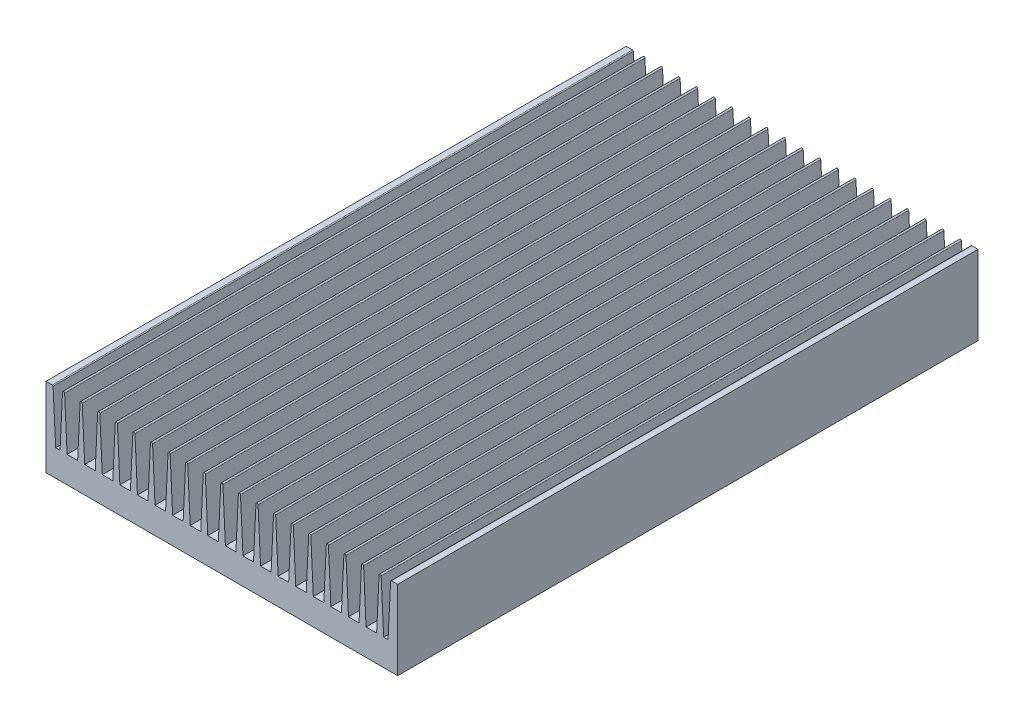
SolidWorks part; units mm, degrees
ref_plane "Спереди" through (0, 0, 0) normal (0, 0, 1) x (1, 0, 0)
ref_plane "Сверху" through (0, 0, 0) normal (0, 1, 0) x (1, 0, 0)
ref_plane "Справа" through (0, 0, 0) normal (1, 0, 0) x (0, 0, -1)
sketch "Эскиз1" plane through (0, 0, 0) normal (0, 0, 1) x (1, 0, 0)
  line L0 (0, 45) -> (3.5244, 45)
  line L1 (0, 0) -> (200, 0)
  line L2 (4.0238, 44.525) -> (5.5, 15)
  line L3 (0, 45) -> (0, 0)
  line L4 (200, 45) -> (200, 0)
  line L5 (100, 63.7127) -> (100, -22.2582) construction
  line L8 (200, 45) -> (196.4756, 45)
  line L9 (195.9762, 44.525) -> (194.5, 15)
  line L10 (5.5, 15) -> (194.5, 15)
  arc A0 (3.5244, 45) -> (4.0238, 44.525) centre (3.5244, 44.5) cw
  arc A2 (196.4756, 45) -> (195.9762, 44.525) centre (196.4756, 44.5) ccw
  point P18 (196, 45)
  dimension "D9" = 0.5
  dimension "D1" = 200
  dimension "D2" = 15
  dimension "D3" = 5.5
  dimension "D4" = 45
  dimension "D7" = 4
extrude "Вытянуть1" add sketch "Эскиз1" along normal blind 330
sketch "Эскиз2" plane through (0, 0, 330) normal (0, 0, 1) x (1, 0, 0)
  line L0 (194.5, 15) -> (5.5, 15) construction
  line L1 (9.4007, 44.4285) -> (8, 15)
  line L2 (10, 45) -> (10, 22.5548) construction
  line L3 (10.5993, 44.4285) -> (12, 15)
  line L4 (8, 15) -> (12, 15)
  line L6 (0, 45) -> (0, 0) construction
  arc A0 (9.4007, 44.4285) -> (10.5993, 44.4285) centre (10, 44.4) cw
  dimension "D1" = 30
  dimension "D3" = 0.6
  dimension "D2" = 4
  dimension "D4" = 10
extrude "Вытянуть3" add sketch "Эскиз2" against normal blind 330
pattern_curve "Кривая1" of "Вытянуть3" along edge at (100, 0, 0) parameters "D1"=19, "D3"=10, "D2"=1, "D4"=50
sketch "Эскиз3" plane through (0, 0, 0) normal (0, -1, 0) x (1, 0, 0)
  line L2 (0, 0) -> (200, 0) construction
  line L3 (0, 330) -> (0, 0) construction
  line L4 (200, 330) -> (200, 0) construction
  circle A0 centre (9.5, 19.5) radius 2.1
  circle A1 centre (11.5, 151) radius 2.1
  circle A2 centre (16.5, 240) radius 2.1
  circle A3 centre (181.5, 210) radius 2.1
  circle A4 centre (188.5, 40) radius 2.1
  circle A5 centre (163.5, 130) radius 2.1
  circle A6 centre (63.5, 189) radius 2.1
  circle A7 centre (39.5, 79.5) radius 2.6
  circle A8 centre (114.5, 30) radius 1.6
  circle A9 centre (16.58, 183.75) radius 2.6
  circle A10 centre (84, 49) radius 1.3
  circle A11 centre (89, 89) radius 1.3
  circle A12 centre (61.5, 170) radius 1.3
  circle A13 centre (61.5, 210) radius 1.3
  circle A14 centre (108.5, 190) radius 1.3
  circle A15 centre (113.5, 220) radius 2.1
  dimension "D1" = 9.5
  dimension "D2" = 19.5
  dimension "D3" = 4.2
  dimension "D7" = 240
  dimension "D8" = 18.5
  dimension "D10" = 11.5
  dimension "D12" = 36.5
  dimension "D16" = 5.2
  dimension "D21" = 3.2
  dimension "D22" = 16.58
  dimension "D23" = 183.75
  dimension "D24" = 2.6
  dimension "D26" = 89
  dimension "D28" = 84
  dimension "D30" = 170
  dimension "D32" = 61.5
  dimension "D34" = 190
  dimension "D35" = 4.2
  dimension "D36" = 180
  dimension "D37" = 75
  dimension "D4" = 151
  dimension "D5" = 11.5
  dimension "D6" = 16.5
  dimension "D9" = 210
  dimension "D11" = 40
  dimension "D13" = 130
  dimension "D14" = 63.5
  dimension "D15" = 189
  dimension "D17" = 39.5
  dimension "D18" = 79.5
  dimension "D19" = 30
  dimension "D20" = 114.5
  dimension "D25" = 89
  dimension "D27" = 49
  dimension "D29" = 210
  dimension "D31" = 61.5
  dimension "D33" = 108.5
extrude "Вырез-Вытянуть1" cut sketch "Эскиз3" against normal blind 8
